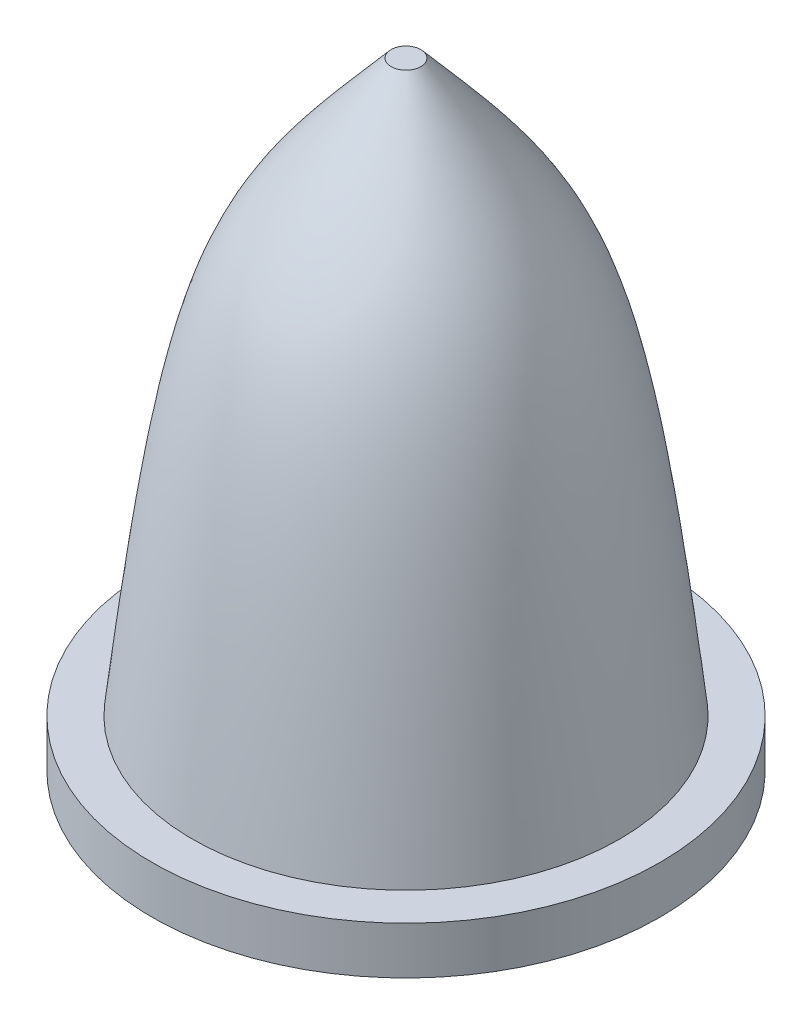
SolidWorks part; units mm, degrees
ref_plane "Front Plane" through (0, 0, 0) normal (0, 0, 1) x (1, 0, 0)
ref_plane "Top Plane" through (0, 0, 0) normal (0, 1, 0) x (1, 0, 0)
ref_plane "Right Plane" through (0, 0, 0) normal (1, 0, 0) x (0, 0, -1)
sketch "Sketch1" plane through (0, 0, 0) normal (0, 0, 1) x (1, 0, 0)
  line L0 (0, -193.5981) -> (0, 9486.3054) construction
  line L1 (0, 3.2626) -> (-2, 3.2626)
  line L2 (-2, 3.2626) -> (-2, 0)
  line L3 (-2, 0) -> (-5.35, 0)
  line L4 (-5.35, 0) -> (-5.35, 1)
  line L5 (-5.35, 1) -> (-4.5, 1)
  line L6 (0, 13) -> (-0.3124, 13)
  line L7 (0, 3.2626) -> (0, 13)
  spline S0 degree 3 poles (-4.5, 1) (-3.548, 9.4621) (-3.1313, 9.7172) (-0.3124, 13) knots 0 0 0 0 0.873329 0.873329 0.873329 0.873329
  dimension "D1" = 13
  dimension "D2" = 5.35
  dimension "D3" = 4.5
  dimension "D4" = 1
  dimension "D5" = 2
revolve "Revolve1" add sketch "Sketch1" angle 360 about L0
